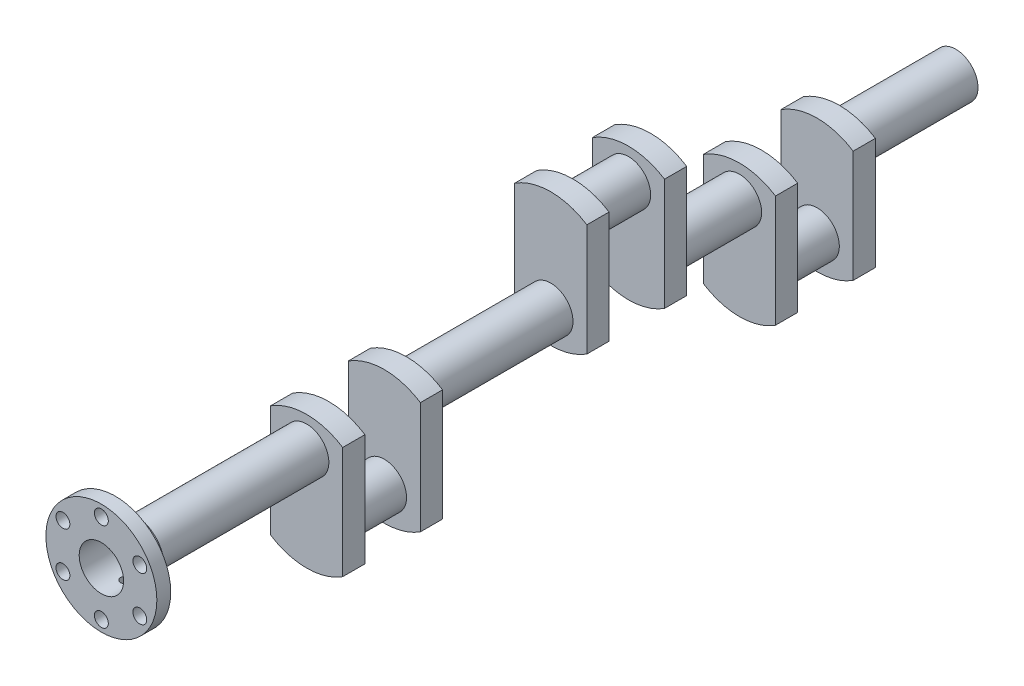
SolidWorks part; units mm, degrees
ref_plane "Front Plane" through (0, 0, 0) normal (0, 0, 1) x (1, 0, 0)
ref_plane "Top Plane" through (0, 0, 0) normal (0, 1, 0) x (1, 0, 0)
ref_plane "Right Plane" through (0, 0, 0) normal (1, 0, 0) x (0, 0, -1)
sketch "Sketch1" plane through (0, 0, 0) normal (0, 0, 1) x (1, 0, 0)
  line L0 (0, 0) -> (0, -20) construction
  line L1 (0, 0) -> (0, 20) construction
  circle A0 centre (0, 0) radius 20
  circle A1 centre (0, 0) radius 16 construction
  circle A2 centre (0, 16) radius 2.5
  circle A3 centre (13.8564, 8) radius 2.5
  circle A4 centre (13.8564, -8) radius 2.5
  circle A5 centre (0, -16) radius 2.5
  circle A6 centre (-13.8564, -8) radius 2.5
  circle A7 centre (-13.8564, 8) radius 2.5
  circle A8 centre (0, 0) radius 8
  point P20 (0, 0)
  dimension "D1" = 40
  dimension "D2" = 6
extrude "Boss-Extrude1" add sketch "Sketch1" along normal blind 5
sketch "Sketch2" plane through (0, 0, 0) normal (0, 0, -1) x (-1, 0, 0)
  circle A0 centre (0, 0) radius 8
  circle A1 centre (0, 0) radius 10.6331
extrude "Boss-Extrude2" add sketch "Sketch2" along normal blind 7 contours A1 | A0
sketch "Sketch3" plane through (0, 0, -7) normal (0, 0, -1) x (-1, 0, 0)
  circle A0 centre (0, 0) radius 8
extrude "Boss-Extrude3" add sketch "Sketch3" along normal blind 62 separate body
sketch "Sketch4" plane through (0, 0, -69) normal (0, 0, -1) x (-1, 0, 0)
  circle A0 centre (0, 0) radius 6
extrude "Boss-Extrude4" add sketch "Sketch4" along normal blind 8
sketch "Sketch5" plane through (0, 0, 0) normal (0, 1, 0) x (1, 0, 0)
  circle A0 centre (0, 3.4019) radius 1.5
extrude "Cut-Extrude2" cut sketch "Sketch5" against normal mid plane 25
sketch "Sketch6" plane through (0, 0, -77) normal (0, 0, -1) x (-1, 0, 0)
  line L6 (13, -25) -> (13, 7.1742)
  line L7 (13, -25) -> (13, -33.1742)
  line L9 (-13, -25) -> (-13, -33.1742)
  line L10 (-13, -25) -> (-13, 7.1742)
  circle A4 centre (0, 0) radius 6
  circle A6 centre (0, -25) radius 6
  arc A7 (13, 7.1742) -> (-13, 7.1742) centre (0, -13) ccw
  arc A8 (-13, -33.1742) -> (13, -33.1742) centre (0, -13) ccw
  dimension "D1" = 48
extrude "Boss-Extrude6" add sketch "Sketch6" against normal blind 8 contours L6 A7 L10 L9 A8 L7 | A6 | A4
sketch "Sketch8" plane through (0, 0, -77) normal (0, 0, -1) x (-1, 0, 0)
  circle A0 centre (0, -25) radius 6
extrude "Boss-Extrude8" add sketch "Sketch8" against normal blind 8
sketch "Sketch9" plane through (0, 0, -77) normal (0, 0, -1) x (-1, 0, 0)
  circle A0 centre (0, -25) radius 8
extrude "Boss-Extrude9" add sketch "Sketch9" along normal blind 20 contours A0
sketch "Sketch10" plane through (0, 0, -97) normal (0, 0, -1) x (-1, 0, 0)
  circle A0 centre (0, -25) radius 6
extrude "Boss-Extrude10" add sketch "Sketch10" along normal blind 8
sketch "Sketch11" plane through (0, 0, -105) normal (0, 0, -1) x (-1, 0, 0)
  line L5 (-13, 7.1742) -> (-13, -33.1742)
  line L6 (13, 7.1742) -> (13, -33.1742)
  circle A0 centre (0, -25) radius 6
  circle A1 centre (0, 0) radius 6
  arc A2 (-13, -33.1742) -> (13, -33.1742) centre (0, -13) ccw
  arc A3 (13, 7.1742) -> (-13, 7.1742) centre (0, -13) ccw
  dimension "D1" = 12
  dimension "D2" = 12
extrude "Boss-Extrude12" add sketch "Sketch11" against normal blind 8
sketch "Sketch12" plane through (0, 0, -105) normal (0, 0, -1) x (-1, 0, 0)
  circle A0 centre (0, 0) radius 6
extrude "Boss-Extrude13" add sketch "Sketch12" against normal blind 8
sketch "Sketch13" plane through (0, 0, -105) normal (0, 0, -1) x (-1, 0, 0)
  circle A1 centre (0, 0) radius 8
extrude "Boss-Extrude14" add sketch "Sketch13" along normal blind 52
sketch "Sketch14" plane through (0, 0, -157) normal (0, 0, -1) x (-1, 0, 0)
  circle A0 centre (0, 0) radius 6
extrude "Boss-Extrude15" add sketch "Sketch14" along normal blind 8
sketch "Sketch15" plane through (0, 0, -165) normal (0, 0, -1) x (-1, 0, 0)
  line L3 (13, 32.6742) -> (13, -7.6742)
  line L4 (13, -33.1742) -> (13, 7.1742) construction
  line L6 (-13, 32.6742) -> (-13, -7.6742)
  circle A0 centre (0, 0) radius 6
  circle A1 centre (0, 25) radius 6
  arc A2 (-13, -7.6742) -> (13, -7.6742) centre (0, 12.5) ccw
  arc A3 (13, 32.6742) -> (-13, 32.6742) centre (0, 12.5) ccw
  dimension "D1" = 12
extrude "Boss-Extrude17" add sketch "Sketch15" against normal blind 8
sketch "Sketch16" plane through (0, 0, -165) normal (0, 0, -1) x (-1, 0, 0)
  circle A0 centre (0, 25) radius 6
extrude "Boss-Extrude18" add sketch "Sketch16" against normal blind 8
sketch "Sketch17" plane through (0, 0, -165) normal (0, 0, -1) x (-1, 0, 0)
  circle A2 centre (0, 25.5) radius 8
extrude "Boss-Extrude23" add sketch "Sketch17" along normal blind 20
sketch "Sketch21" plane through (0, 0, -185) normal (0, 0, -1) x (-1, 0, 0)
  circle A1 centre (0, 25.5) radius 6
extrude "Boss-Extrude24" add sketch "Sketch21" along normal blind 8
sketch "Sketch22" plane through (0, 0, -193) normal (0, 0, -1) x (-1, 0, 0)
  line L2 (-13, 32.9242) -> (-13, -7.6742)
  line L3 (-13, -7.6742) -> (-12.6097, -7.6705)
  line L4 (13, -33.1742) -> (13, 7.1742) construction
  line L5 (13, -7.4242) -> (13, 32.6742)
  line L6 (13, 32.6742) -> (13, 32.9242)
  circle A0 centre (0, 25.5) radius 6
  arc A1 (-13, -7.4242) -> (13, -7.4242) centre (0, 12.75) ccw
  arc A2 (13, 32.9242) -> (-13, 32.9242) centre (0, 12.75) ccw
  circle M3 centre (0, 25.5) radius 6
  dimension "D1" = 12
extrude "Boss-Extrude26" add sketch "Sketch22" against normal blind 8 contours L6 A2 L2 A1 L5 M3
sketch "Sketch24" plane through (0, 0, -193) normal (0, 0, -1) x (-1, 0, 0)
  line L0 (13, -7.6742) -> (13, 32.9242)
  line L1 (-13, 32.9242) -> (-13, -7.4242)
  arc A2 (13, 32.9242) -> (-13, 32.9242) centre (0, 12.75) ccw
  circle A3 centre (0, 0) radius 8
  arc A4 (-13, -7.4242) -> (13, -7.4242) centre (0, 12.75) ccw
extrude "Boss-Extrude27" add sketch "Sketch24" along normal blind 32 contours A3
sketch "Sketch25" plane through (0, 0, -225) normal (0, 0, -1) x (-1, 0, 0)
  circle A0 centre (0, 0) radius 6
extrude "Boss-Extrude28" add sketch "Sketch25" along normal blind 8
sketch "Sketch26" plane through (0, 0, -233) normal (0, 0, -1) x (-1, 0, 0)
  line L2 (13, 7.6742) -> (13, -32.6742)
  line L5 (-13, 7.6742) -> (-13, -32.6742)
  line L6 (-13, 7.1742) -> (-13, -33.1742) construction
  arc A1 (13, 7.6742) -> (-13, 7.6742) centre (0, -12.5) ccw
  circle A2 centre (0, 0) radius 6
  arc A3 (-13, -32.6742) -> (13, -32.6742) centre (0, -12.5) ccw
extrude "Boss-Extrude31" add sketch "Sketch26" against normal blind 8
sketch "Sketch27" plane through (0, 0, -233) normal (0, 0, -1) x (-1, 0, 0)
  circle A0 centre (0, -24.5) radius 8
extrude "Boss-Extrude32" add sketch "Sketch27" along normal blind 20
sketch "Sketch28" plane through (0, 0, -253) normal (0, 0, -1) x (-1, 0, 0)
  circle A0 centre (0, -24.5) radius 6
extrude "Boss-Extrude33" add sketch "Sketch28" along normal blind 8
sketch "Sketch29" plane through (0, 0, -261) normal (0, 0, -1) x (-1, 0, 0)
  line L3 (-13, 7.6742) -> (-13, -32.6742)
  line L4 (13, 7.6742) -> (13, -32.6742)
  arc A0 (-13, -32.6742) -> (13, -32.6742) centre (0, -12.5) ccw
  arc A1 (13, 7.6742) -> (-13, 7.6742) centre (0, -12.5) ccw
  circle A2 centre (0, -24.5) radius 6
extrude "Boss-Extrude34" add sketch "Sketch29" against normal blind 8
sketch "Sketch30" plane through (0, 0, -261) normal (0, 0, -1) x (-1, 0, 0)
  circle A0 centre (0, 0) radius 8
extrude "Boss-Extrude35" add sketch "Sketch30" along normal blind 42
